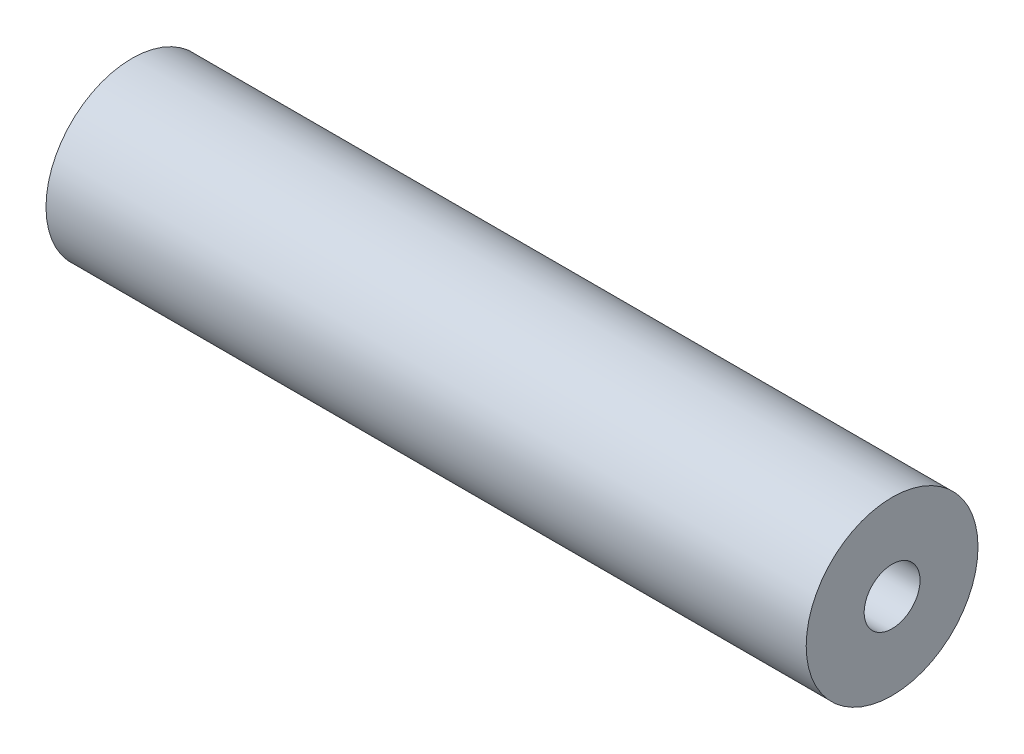
SolidWorks part; units mm, degrees
material "1060 合金"
ref_plane "正面" through (0, 0, 0) normal (0, 0, 1) x (1, 0, 0)
ref_plane "平面" through (0, 0, 0) normal (0, 1, 0) x (1, 0, 0)
ref_plane "右側面" through (0, 0, 0) normal (1, 0, 0) x (0, 0, -1)
sketch "ｽｹｯﾁ1" plane through (0, 0, 0) normal (1, 0, 0) x (0, 0, -1)
  circle A0 centre (0, 0) radius 4
  dimension "D1" = 8
extrude "ﾎﾞｽ - 押し出し1" add sketch "ｽｹｯﾁ1" along normal blind 35.4
sketch "ｽｹｯﾁ2" plane through (35.4, 0, 0) normal (1, 0, 0) x (0, 0, -1)
  circle A0 centre (0, 0) radius 1.3
  dimension "D1" = 2.6
extrude "ｶｯﾄ - 押し出し1" cut sketch "ｽｹｯﾁ2" against normal blind 12
sketch "ｽｹｯﾁ3" plane through (0, 0, 0) normal (-1, 0, 0) x (0, 0, 1)
  circle A0 centre (0, 0) radius 1.3
  dimension "D1" = 2.6
extrude "ｶｯﾄ - 押し出し2" cut sketch "ｽｹｯﾁ3" against normal blind 12
